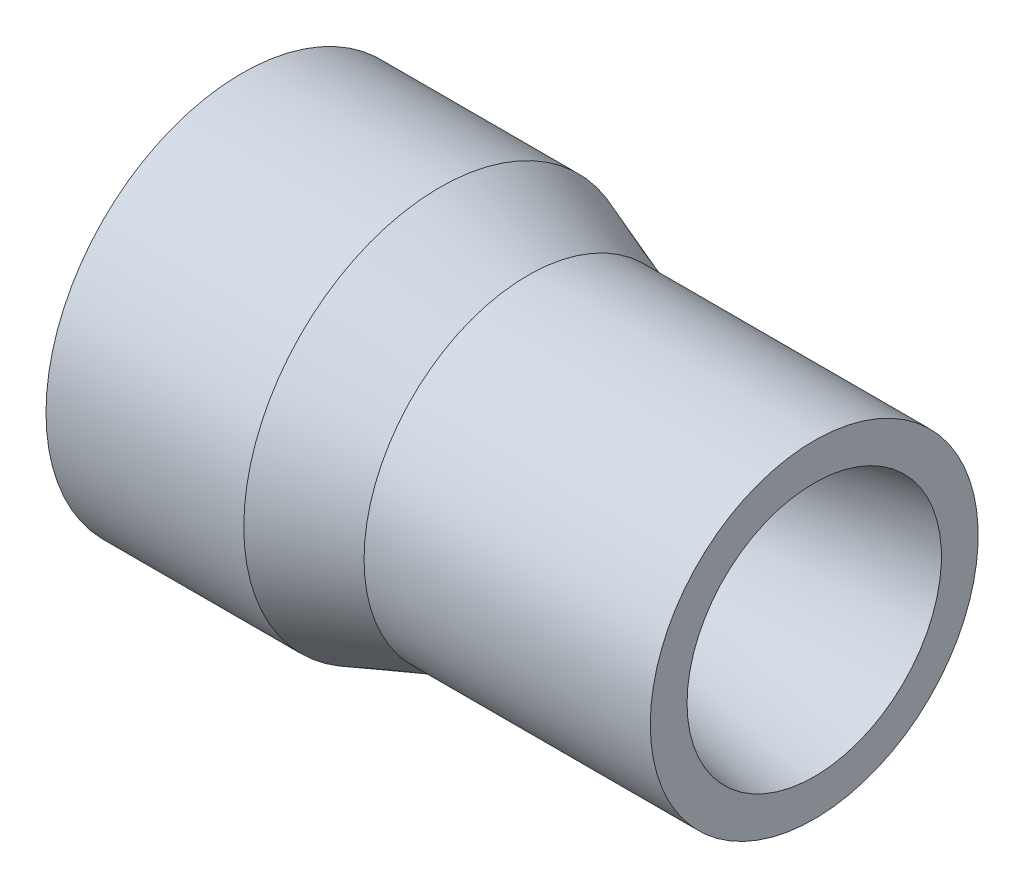
SolidWorks part; units mm, degrees
ref_plane "Front Plane" through (0, 0, 0) normal (0, 0, 1) x (1, 0, 0)
ref_plane "Top Plane" through (0, 0, 0) normal (0, 1, 0) x (1, 0, 0)
ref_plane "Right Plane" through (0, 0, 0) normal (1, 0, 0) x (0, 0, -1)
sketch "Sketch1" plane through (0, 0, 0) normal (0, 0, 1) x (1, 0, 0)
  line L0 (0, 0) -> (176.8872, 0) construction
  line L1 (0, 41.295) -> (27.5254, 41.295) construction
  line L2 (54.4274, 15.285) -> (96.5346, 15.285) construction
  line L3 (42.9453, 29.8255) -> (62.8124, 18.3553)
  line L7 (0, 41.295) -> (0, 50.82)
  line L11 (75.9338, 15.5588) -> (94.1128, 21.868) construction
  line L13 (148.34, 32.975) -> (123.4215, 29.4729) construction
  line L14 (148.34, 32.975) -> (148.34, 42.5)
  line L15 (148.34, 42.5) -> (74.13, 42.5)
  line L17 (74.13, 42.5) -> (51.271, 50.82)
  line L18 (51.271, 50.82) -> (0, 50.82)
  arc A0 (0, 41.295) -> (42.9453, 29.8255) centre (0.1403, -44.3149) cw
  arc A1 (74.13, 15.285) -> (62.8124, 18.3553) centre (74.2724, 38.2046) cw
  arc A2 (74.13, 15.285) -> (75.9338, 15.5588) centre (74.1663, 21.1249) ccw
  spline S0 degree 3 poles (75.9338, 15.5588) (97.1242, 22.9132) (126.0123, 29.837) (148.34, 32.975) knots 0 0 0 0 1 1 1 1
  point P14 (0, 0)
  dimension "D4" = 22.92
  dimension "D5" = 74.13
  dimension "D7" = 5.84
  dimension "D11" = 9.525
  dimension "D6" = 30
  dimension "D3" = 85.61
  dimension "D9" = 74.21
  dimension "D1" = 41.295
  dimension "D2" = 15.285
  dimension "D8" = 19.14
  dimension "D10" = 32.975
  dimension "D12" = 8
  dimension "D13" = 9.525
  dimension "D14" = 20
revolve "Revolve1" add sketch "Sketch1" angle 360 about L0
